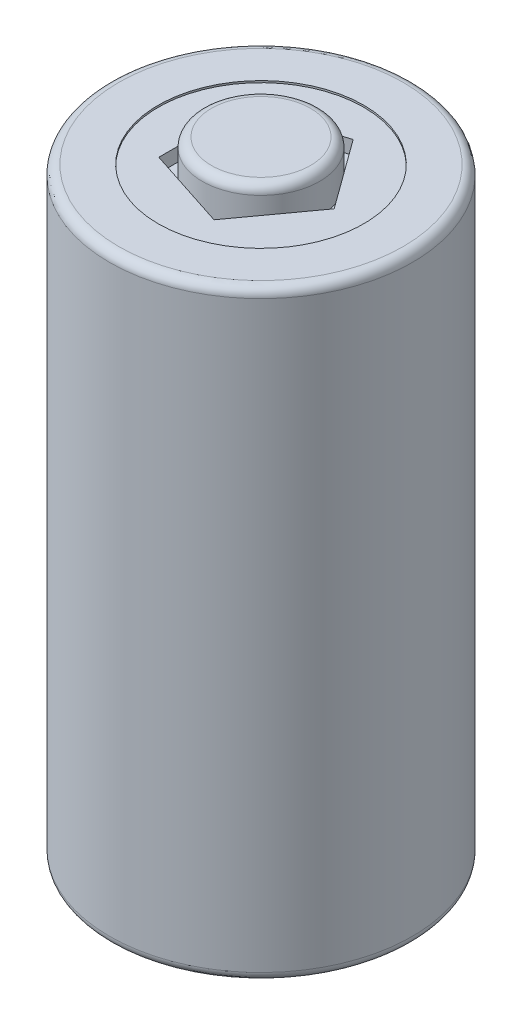
SolidWorks part; units mm, degrees
ref_plane "Plane1" through (0, 0, 0) normal (0, 0, 1) x (1, 0, 0)
ref_plane "Plane2" through (0, 0, 0) normal (0, 1, 0) x (1, 0, 0)
ref_plane "Plane3" through (0, 0, 0) normal (1, 0, 0) x (0, 0, -1)
sketch "Sketch1" plane through (0, 0, 0) normal (0, 0, 1) x (1, 0, 0)
  line L0 (0, -16.4) -> (0, 16.4) construction
  line L1 (0, 16.4) -> (8.25, 16.4)
  line L2 (0, -16.4) -> (0, 16.4)
  line L3 (0, -16.4) -> (8.25, -16.4)
  line L4 (8.25, 16.4) -> (8.25, -16.4)
  dimension "D1" = 8.25
  dimension "D2" = 32.8
revolve "Base-Revolve" add sketch "Sketch1" angle 360 about L0
sketch "Sketch2" plane through (0, -16.4, 0) normal (0, -1, 0) x (1, 0, 0)
  circle A0 centre (0, 0) radius 5.6
  dimension "D1" = 11.2
extrude "Cut-Extrude1" cut sketch "Sketch2" against normal blind 0.75
sketch "Sketch3" plane through (0, 16.4, 0) normal (0, 1, 0) x (-1, 0, 0)
  circle A1 centre (0, 0) radius 5.6
  circle A2 centre (0, 0) radius 5.6
  dimension "D1" = 0
extrude "Cut-Extrude2" cut sketch "Sketch3" against normal blind 0.1
sketch "Sketch4" plane through (0, 16.3, 0) normal (0, 1, 0) x (-1, 0, 0)
  line L0 (3.225, -2.3431) -> (3.225, 2.3431)
  line L1 (3.225, 2.3431) -> (-1.2318, 3.7912)
  line L2 (-1.2318, 3.7912) -> (-3.9863, 0)
  line L3 (-3.9863, 0) -> (-1.2318, -3.7912)
  line L4 (-1.2318, -3.7912) -> (3.225, -2.3431)
  circle A0 centre (0, 0) radius 3.225 construction
  dimension "D1" = 6.45
extrude "Cut-Extrude3" cut sketch "Sketch4" against normal blind 0.75
sketch "Sketch5" plane through (0, 15.55, 0) normal (0, 1, 0) x (-1, 0, 0)
  circle A1 centre (0, 0) radius 3.2
  dimension "D1" = 6.4
extrude "Boss-Extrude3" add sketch "Sketch5" along normal offset from surface (2.15 mm away) 34.1
fillet "Fillet1" radius 0.5 1 edges at (0, 17.7, -3.2)
ref_plane "Plane4" through (0, -16.3, 0) normal (0, -1, 0) x (1, 0, 0)
sketch "Sketch6" plane through (0, -16.3, 0) normal (0, -1, 0) x (1, 0, 0)
  circle A1 centre (0, 0) radius 5.6 construction
  circle A2 centre (0, 0) radius 6.1
  circle A3 centre (0, 0) radius 6.1
  circle A4 centre (0, 0) radius 5.6
  dimension "D1" = 0.5
extrude "Cut-Extrude4" cut sketch "Sketch6" against normal up to surface (0.65 mm away) up to face at (0, -15.65, -5.6)
fillet "Fillet2" radius 0.5 2 edges at (0, -16.4, -8.25) (0, 16.4, -8.25)
